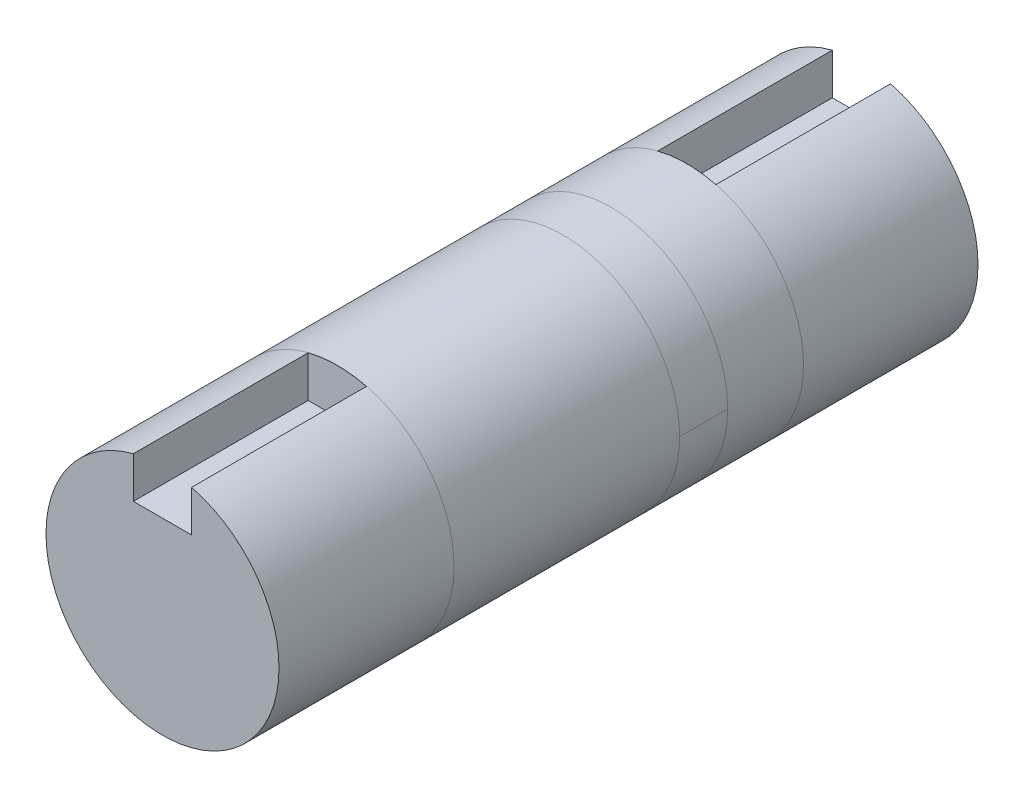
SolidWorks part; units mm, degrees
material "1023 Carbon Steel Sheet (SS)"
ref_plane "Front Plane" through (0, 0, 0) normal (0, 0, 1) x (1, 0, 0)
ref_plane "Top Plane" through (0, 0, 0) normal (0, 1, 0) x (1, 0, 0)
ref_plane "Right Plane" through (0, 0, 0) normal (1, 0, 0) x (0, 0, -1)
sketch "Sketch1" plane through (0, 0, 0) normal (0, 0, 1) x (1, 0, 0)
  circle A0 centre (0, 0) radius 100
  dimension "D1" = 200
extrude "Boss-Extrude1" add sketch "Sketch1" against normal blind 600
sketch "Sketch2" plane through (0, 0, 0) normal (0, 0, 1) x (1, 0, 0)
  line L1 (-25, 61.4) -> (25, 61.4)
  line L2 (-25, 61.4) -> (-25, 111.4)
  line L3 (-25, 111.4) -> (25, 111.4)
  line L4 (25, 61.4) -> (25, 111.4)
  line L5 (-25, 61.4) -> (25, 111.4) construction
  line L6 (-25, 111.4) -> (25, 61.4) construction
  point P0 (0, 86.4)
  dimension "D1" = 50
  dimension "D2" = 111.4
extrude "Cut-Extrude1" cut sketch "Sketch2" against normal blind 150
sketch "Sketch3" plane through (0, 0, -600) normal (0, 0, -1) x (-1, 0, 0)
  line L1 (-25, 61.4) -> (25, 61.4)
  line L2 (-25, 61.4) -> (-25, 111.4)
  line L3 (-25, 111.4) -> (25, 111.4)
  line L4 (25, 61.4) -> (25, 111.4)
  line L5 (-25, 61.4) -> (25, 111.4) construction
  line L6 (-25, 111.4) -> (25, 61.4) construction
  point P0 (0, 86.4)
  dimension "D1" = 50
  dimension "D2" = 111.4
extrude "Cut-Extrude2" cut sketch "Sketch3" against normal blind 150
sketch "Sketch5" plane through (0, 0, 0) normal (0, 1, 0) x (1, 0, 0)
  line L0 (-100, 600) -> (-100, 0) construction
  line L2 (-100, 385.1108) -> (100, 385.1108)
  line L3 (-100, 385.1108) -> (-100, 343.8955)
  line L4 (-100, 343.8955) -> (100, 343.8955)
  line L5 (100, 385.1108) -> (100, 343.8955)
  line L6 (100, 0) -> (100, 600) construction
  line L7 (-100, 450.1828) -> (100, 450.1828)
  line L10 (-100, 150.2899) -> (100, 150.2899)
split line "Split Line1"
